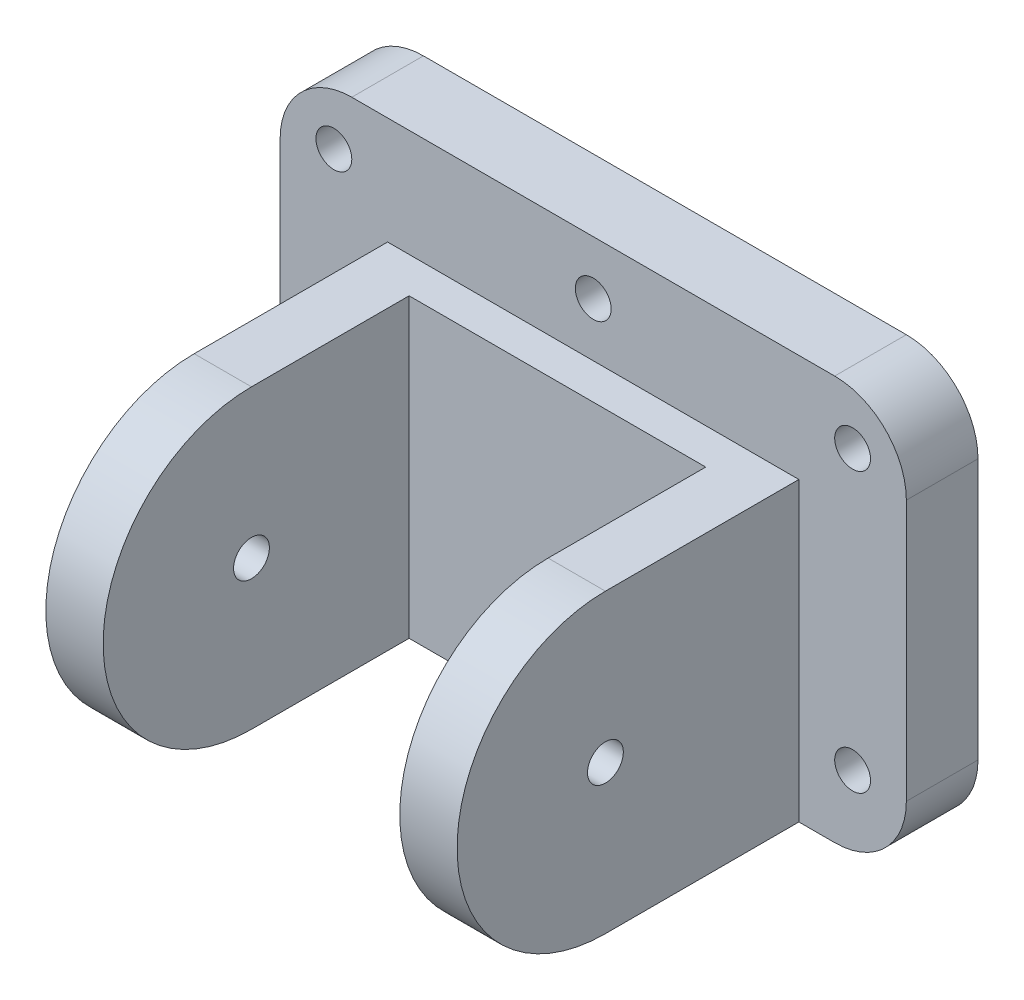
SolidWorks part; units mm, degrees
ref_plane "Front Plane" through (0, 0, 0) normal (0, 0, 1) x (1, 0, 0)
ref_plane "Top Plane" through (0, 0, 0) normal (0, 1, 0) x (1, 0, 0)
ref_plane "Right Plane" through (0, 0, 0) normal (1, 0, 0) x (0, 0, -1)
sketch "Sketch1" plane through (0, 0, 0) normal (0, 0, 1) x (1, 0, 0)
  line L1 (-12.7, 12.7) -> (12.7, 12.7) construction
  line L2 (-12.7, 12.7) -> (-12.7, -12.7) construction
  line L3 (-12.7, -12.7) -> (12.7, -12.7) construction
  line L4 (12.7, 12.7) -> (12.7, -12.7) construction
  line L5 (-12.7, 12.7) -> (12.7, -12.7) construction
  line L6 (-12.7, -12.7) -> (12.7, 12.7) construction
  line L7 (-28.7, 20.7) -> (28.7, 20.7)
  line L8 (-28.7, 20.7) -> (-28.7, -20.7)
  line L9 (-28.7, -20.7) -> (28.7, -20.7)
  line L10 (28.7, 20.7) -> (28.7, -20.7)
  line L11 (-28.7, 20.7) -> (28.7, -20.7) construction
  line L12 (-28.7, -20.7) -> (28.7, 20.7) construction
  point P0 (0, 0)
  point P6 (0, 0)
  dimension "D1" = 25.4
  dimension "D2" = 25.4
  dimension "D3" = 16
  dimension "D4" = 8
  dimension "D5" = 8
extrude "Boss-Extrude1" add sketch "Sketch1" along normal blind 10
sketch "Sketch2" plane through (0, 0, 10) normal (0, 0, 1) x (1, 0, 0)
  line L5 (-28.7, 20.7) -> (28.7, 20.7)
  line L6 (-28.7, 20.7) -> (-28.7, -20.7)
  line L7 (-28.7, -20.7) -> (28.7, -20.7)
  line L8 (28.7, 20.7) -> (28.7, -20.7)
  line L9 (-28.7, 20.7) -> (28.7, -20.7) construction
  line L10 (-28.7, -20.7) -> (28.7, 20.7) construction
  point P0 (0, 0)
  point P1 (0, 0)
extrude "Boss-Extrude2" add sketch "Sketch2" along normal blind 5
sketch "Sketch4" plane through (28.7, 0, 0) normal (1, 0, 0) x (0, 0, -1)
  line L0 (-15, -20.7) -> (0, -20.7) construction
  line L1 (-15, -20.7) -> (-15, 20.7)
  line L2 (-15, 20.7) -> (-37, 20.7)
  line L3 (-15, -20.7) -> (-37, -20.7)
  arc A1 (-37, -20.7) -> (-37, 20.7) centre (-37, 0) cw
  dimension "D1" = 22
extrude "Boss-Extrude3" add sketch "Sketch4" against normal blind 8
sketch "Sketch5" plane through (-28.7, 0, 0) normal (-1, 0, 0) x (0, 0, 1)
  line L0 (15, 20.7) -> (15, -20.7)
  line L1 (15, -20.7) -> (37, -20.7)
  line L2 (15, 20.7) -> (37, 20.7)
  arc A0 (37, 20.7) -> (37, -20.7) centre (37, 0) cw
extrude "Boss-Extrude4" add sketch "Sketch5" against normal blind 8
sketch "Sketch6" plane through (28.7, 0, 0) normal (1, 0, 0) x (0, 0, -1)
  circle A0 centre (-37, 0) radius 2.5
  dimension "D1" = 5
extrude "Cut-Extrude1" cut sketch "Sketch6" against normal up to surface (57.4 mm away) up to face at (-28.7, 0, 23.675)
sketch "Sketch11" plane through (-28.7, 0, 0) normal (-1, 0, 0) x (0, 0, 1)
  line L0 (37, -20.7) -> (0, -20.7) construction
  line L1 (0, 20.7) -> (10, 20.7)
  line L2 (0, 20.7) -> (0, -20.7)
  line L3 (0, -20.7) -> (10, -20.7)
  line L4 (10, 20.7) -> (10, -20.7)
  dimension "D1" = 10
extrude "Boss-Extrude5" add sketch "Sketch11" along normal blind 15
sketch "Sketch12" plane through (28.7, 0, 0) normal (1, 0, 0) x (0, 0, -1)
  line L0 (-37, -20.7) -> (0, -20.7) construction
  line L1 (0, 20.7) -> (-10, 20.7)
  line L2 (0, 20.7) -> (0, -20.7)
  line L3 (0, -20.7) -> (-10, -20.7)
  line L4 (-10, 20.7) -> (-10, -20.7)
  dimension "D1" = 10
extrude "Boss-Extrude6" add sketch "Sketch12" along normal blind 15
sketch "Sketch13" plane through (0, 20.7, 0) normal (0, 1, 0) x (1, 0, 0)
  line L1 (-43.7, 0) -> (43.7, 0)
  line L2 (-43.7, 0) -> (-43.7, -10)
  line L3 (-43.7, -10) -> (43.7, -10)
  line L4 (43.7, 0) -> (43.7, -10)
extrude "Boss-Extrude7" add sketch "Sketch13" along normal blind 15
sketch "Sketch14" plane through (0, 0, 10) normal (0, 0, 1) x (1, 0, 0)
  line L0 (-43.7, -20.7) -> (-43.7, 35.7) construction
  line L1 (43.7, 35.7) -> (43.7, -20.7) construction
  line L2 (-43.7, -20.7) -> (-28.7, -20.7) construction
  line L3 (43.7, -20.7) -> (28.7, -20.7) construction
  line L4 (-43.7, 35.7) -> (43.7, 35.7) construction
  circle A0 centre (-36.2, -10.7) radius 2.5
  circle A1 centre (-36.2, 28.2) radius 2.5
  circle A2 centre (36.2, 28.2) radius 2.5
  circle A3 centre (36.2, -10.7) radius 2.5
  circle A4 centre (0, 28.2) radius 2.5
  dimension "D1" = 5
  dimension "D2" = 7.5
  dimension "D3" = 7.5
  dimension "D4" = 10
  dimension "D5" = 10
  dimension "D6" = 7.5
  dimension "D7" = 7.5
  dimension "D8" = 7.5
  dimension "D9" = 7.5
  dimension "D10" = 7.5
  dimension "D11" = 72.4
  dimension "D12" = 36.2
extrude "Cut-Extrude2" cut sketch "Sketch14" against normal up to surface (10 mm away) up to face at (0, 7.5, 0)
fillet "Fillet1" radius 10 4 edges at (43.7, -20.7, 5) (-43.7, -20.7, 5) (-43.7, 35.7, 5) (43.7, 35.7, 5)
